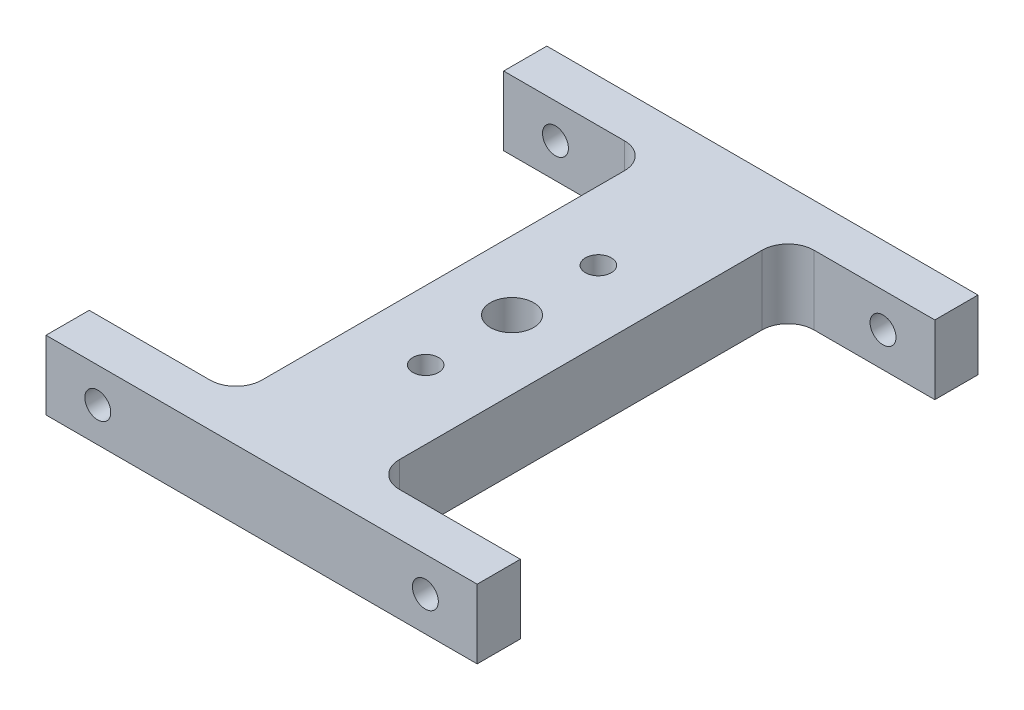
SolidWorks part; units mm, degrees
material "AISI 304"
ref_plane "前视基准面" through (0, 0, 0) normal (0, 0, 1) x (1, 0, 0)
ref_plane "上视基准面" through (0, 0, 0) normal (0, 1, 0) x (1, 0, 0)
ref_plane "右视基准面" through (0, 0, 0) normal (1, 0, 0) x (0, 0, -1)
sketch "草图1" plane through (0, 0, 0) normal (0, 0, 1) x (1, 0, 0)
  line L0 (-24.9678, 110) -> (-24.9678, -110) construction
  line L1 (24.9678, 110) -> (-24.9678, 110)
  line L2 (24.9678, 110) -> (24.9678, 102)
  line L3 (24.9678, 102) -> (-24.9678, 102)
  line L4 (-24.9678, 110) -> (-24.9678, 102)
  dimension "D1" = 8
extrude "凸台-拉伸1" add sketch "草图1" along normal up to vertex (58 mm away)
sketch "草图2" plane through (0, 110, 0) normal (0, 1, 0) x (1, 0, 0)
  line L0 (24.9678, -58) -> (-24.9678, 0) construction
  line L1 (27.5, -58) -> (-22.5, -58) construction
  line L2 (24.9678, -58) -> (-24.9678, -58) construction
  line L3 (-24.9678, -58) -> (24.9678, 0) construction
  line L4 (27.5, 0) -> (-22.5, 0) construction
  line L5 (24.9678, -58) -> (24.9678, 0) construction
  line L6 (0, -58) -> (0, 0) construction
  line L7 (24.9678, -53) -> (10.9678, -53)
  line L8 (24.9678, -53) -> (24.9678, -5)
  line L9 (24.9678, -5) -> (10.9678, -5)
  line L10 (7.9678, -50) -> (7.9678, -8)
  line L11 (24.9678, 0) -> (-24.9678, 0) construction
  line L12 (24.9678, -58) -> (-24.9678, -58) construction
  line L13 (24.9678, 0) -> (-24.9678, 0) construction
  line L14 (-7.9678, -50) -> (-7.9678, -8)
  line L15 (-24.9678, -5) -> (-10.9678, -5)
  line L16 (-24.9678, -53) -> (-24.9678, -5)
  line L17 (-24.9678, -53) -> (-10.9678, -53)
  circle A0 centre (0, -29) radius 2.5
  circle A1 centre (0, -39) radius 1.5
  circle A2 centre (0, -19) radius 1.5
  arc A3 (10.9678, -5) -> (7.9678, -8) centre (10.9678, -8) ccw
  arc A4 (10.9678, -53) -> (7.9678, -50) centre (10.9678, -50) cw
  arc A5 (-10.9678, -53) -> (-7.9678, -50) centre (-10.9678, -50) ccw
  arc A6 (-10.9678, -5) -> (-7.9678, -8) centre (-10.9678, -8) cw
  dimension "D1" = 5
  dimension "D2" = 10
  dimension "D3" = 10
  dimension "D4" = 3
  dimension "D5" = 3
  dimension "D9" = 3
  dimension "D6" = 5
  dimension "D7" = 5
  dimension "D8" = 17
extrude "切除-拉伸1" cut sketch "草图2" against normal blind 10
sketch "草图3" plane through (0, 0, 5) normal (0, 0, 1) x (1, 0, 0)
  line L0 (24.9678, 106) -> (-24.9678, 106) construction
  line L1 (24.9678, 102) -> (24.9678, 110) construction
  line L2 (-24.9678, 102) -> (-24.9678, 110) construction
  circle A0 centre (18.9678, 106) radius 1.5
  circle A1 centre (-18.9678, 106) radius 1.5
  dimension "D1" = 3
  dimension "D2" = 3
  dimension "D3" = 6
  dimension "D4" = 6
extrude "切除-拉伸2" cut sketch "草图3" against normal blind 7 and the other way blind 53
chamfer "倒角1" distance 1.5 angle 45 2 edges at (0, 102, 20.5) (0, 102, 40.5)
